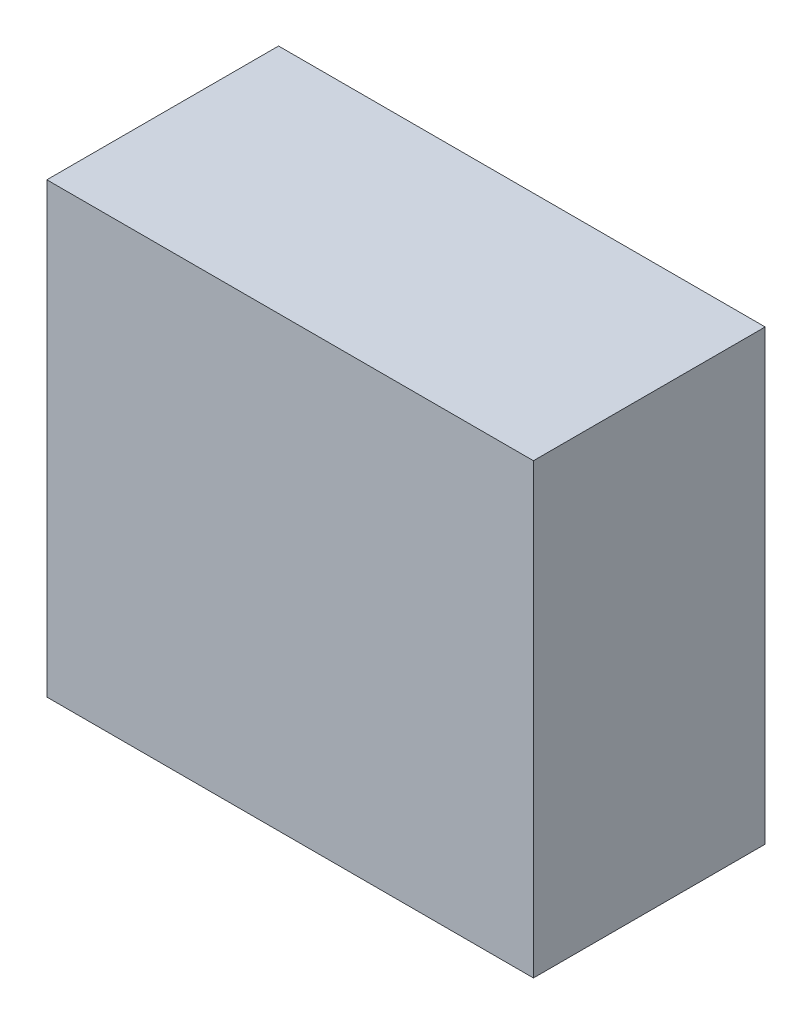
SolidWorks part; units mm, degrees
ref_plane "Front Plane" through (0, 0, 0) normal (0, 0, 1) x (1, 0, 0)
ref_plane "Top Plane" through (0, 0, 0) normal (0, 1, 0) x (1, 0, 0)
ref_plane "Right Plane" through (0, 0, 0) normal (1, 0, 0) x (0, 0, -1)
sketch "Sketch1" plane through (0, 0, 0) normal (0, 0, 1) x (1, 0, 0)
  line L1 (-31.5, 29) -> (31.5, 29)
  line L2 (-31.5, 29) -> (-31.5, -29)
  line L3 (-31.5, -29) -> (31.5, -29)
  line L4 (31.5, 29) -> (31.5, -29)
  line L5 (-31.5, 29) -> (31.5, -29) construction
  line L6 (-31.5, -29) -> (31.5, 29) construction
  point P0 (0, 0)
  dimension "D1" = 63
  dimension "D2" = 58
extrude "Boss-Extrude1" add sketch "Sketch1" along normal blind 30
